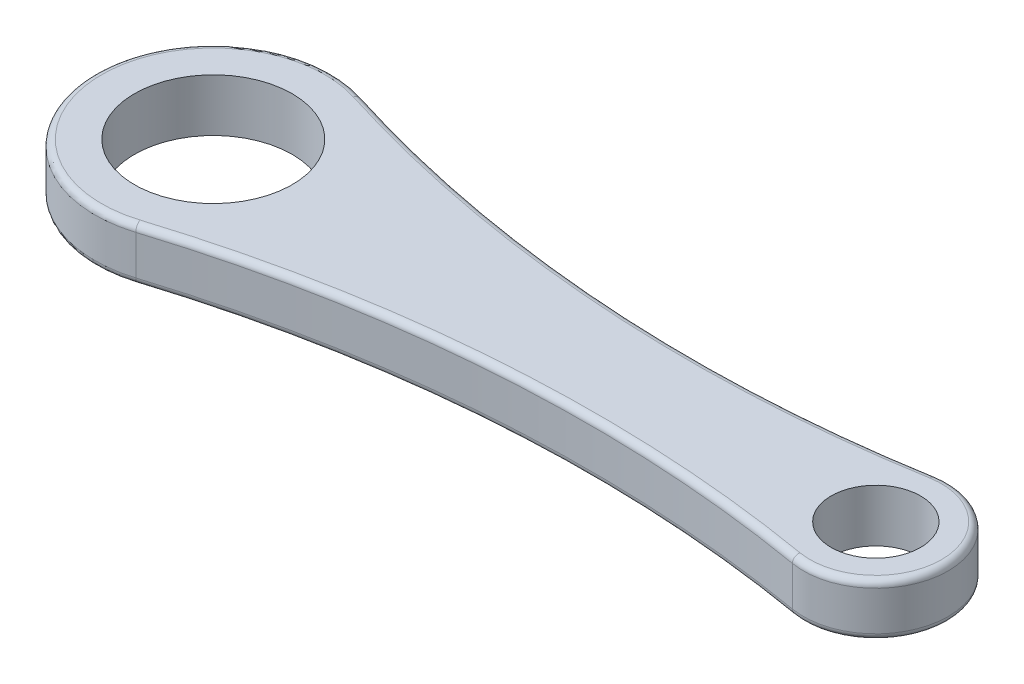
SolidWorks part; units mm, degrees
ref_plane "前视基准面" through (0, 0, 0) normal (0, 0, 1) x (1, 0, 0)
ref_plane "上视基准面" through (0, 0, 0) normal (0, 1, 0) x (1, 0, 0)
ref_plane "右视基准面" through (0, 0, 0) normal (1, 0, 0) x (0, 0, -1)
sketch "草图1" plane through (0, 0, 0) normal (0, 1, 0) x (1, 0, 0)
  line L0 (0, 0) -> (50.4, 0) construction
  circle A0 centre (0, 0) radius 6
  circle A1 centre (50.4, 0) radius 3.4
  arc A2 (2.6926, 8.5878) -> (2.6926, -8.5878) centre (0, 0) ccw
  arc A3 (49.4765, -5.4219) -> (49.4765, 5.4219) centre (50.4, 0) ccw
  arc A4 (2.6926, 8.5878) -> (49.4765, 5.4219) centre (32.6592, 104.1622) ccw
  arc A5 (2.6926, -8.5878) -> (49.4765, -5.4219) centre (32.6592, -104.1622) cw
  dimension "D1" = 18
  dimension "D2" = 11
  dimension "D3" = 6.8
  dimension "D4" = 12
  dimension "D5" = 41
  dimension "D6" = 8
extrude "凸台-拉伸1" add sketch "草图1" along normal blind 4
fillet "圆角1" radius 0.5 8 edges at (-9, 0, 0) (25.8967, 0, -4.2285) (55.9, 0, 0) (-9, 4, 0) (25.8967, 4, -4.2285) (55.9, 4, 0) (25.8967, 0, 4.2285) (25.8967, 4, 4.2285)
